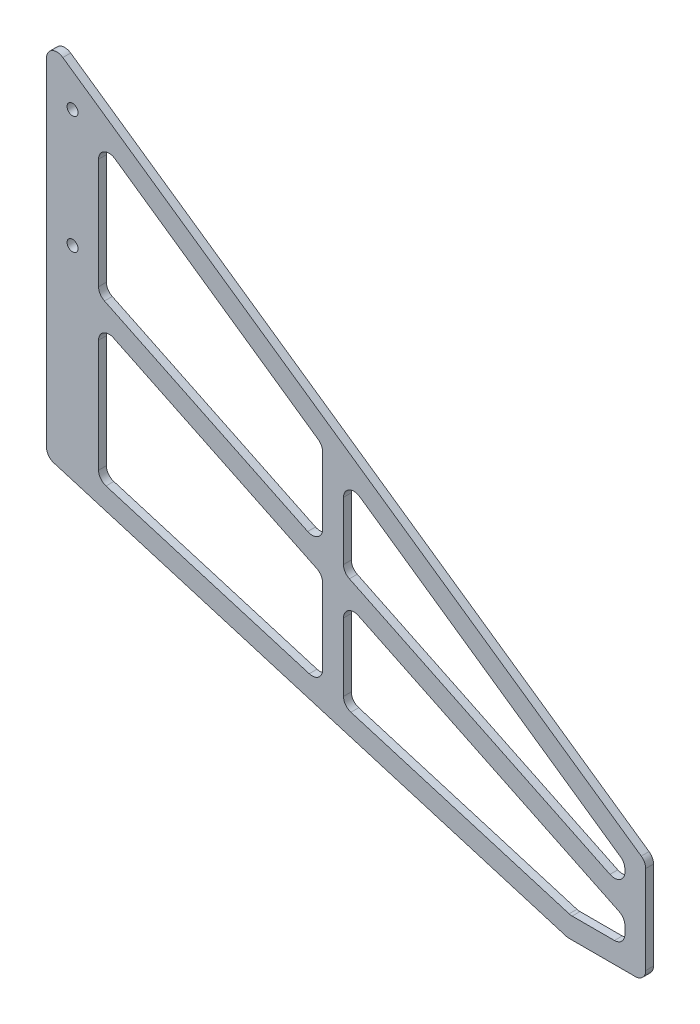
SolidWorks part; units mm, degrees
ref_plane "Спереди" through (0, 0, 0) normal (0, 0, 1) x (1, 0, 0)
ref_plane "Сверху" through (0, 0, 0) normal (0, 1, 0) x (1, 0, 0)
ref_plane "Справа" through (0, 0, 0) normal (1, 0, 0) x (0, 0, -1)
sketch "Эскиз1" plane through (0, 0, 0) normal (0, 0, 1) x (1, 0, 0)
  line L5 (0, 0) -> (0, 140)
  line L10 (0, 140) -> (230, -20)
  line L11 (230, -20) -> (230, -60)
  line L12 (230, -60) -> (200, -60)
  line L13 (200, -60) -> (0, 0)
  dimension "D1" = 230
  dimension "D2" = 40
  dimension "D3" = 30
  dimension "D4" = 140
  dimension "D5" = 60
extrude "Бобышка-Вытянуть1" add sketch "Эскиз1" along normal blind 3
sketch "Эскиз2" plane through (0, 0, 3) normal (0, 0, 1) x (1, 0, 0)
  line L0 (0, 140) -> (0, 0) construction
  circle A0 centre (10, 75) radius 2.1
  circle A1 centre (10, 120.2) radius 2.1
  dimension "D1" = 4.2
  dimension "D2" = 75
  dimension "D3" = 10
  dimension "D4" = 4.2
  dimension "D5" = 45.2
  dimension "D6" = 10
extrude "Вырез-Вытянуть1" cut sketch "Эскиз2" against normal blind 39
sketch "Эскиз5" plane through (0, 0, 3) normal (0, 0, 1) x (1, 0, 0)
  line L0 (222, -24.1801) -> (222, -33.649)
  line L1 (230, -60) -> (230, -20) construction
  line L2 (20, 59.3469) -> (222, -38.0901) construction
  line L3 (20, 63.788) -> (106, 22.3049)
  line L4 (20, 54.9059) -> (106, 13.4228)
  line L5 (20, 116.3416) -> (20, 63.788)
  line L6 (0, 140) -> (0, 0) construction
  line L7 (110, 53.7329) -> (110, -24.6478) construction
  line L8 (114, 50.9503) -> (114, 18.446)
  line L9 (106, 56.5155) -> (106, 22.3049)
  line L10 (8, 5.9522) -> (201.1742, -52)
  line L11 (201.1742, -52) -> (222, -52)
  line L12 (222, -52) -> (222, -24.1801)
  line L13 (222, -24.1801) -> (8, 124.6894)
  line L14 (8, 124.6894) -> (8, 5.9522)
  line L15 (20, 2.3522) -> (106, -23.4478)
  line L16 (201.1742, -52) -> (222, -52)
  line L18 (222, -24.1801) -> (114, 50.9503)
  line L20 (114, 18.446) -> (222, -33.649)
  line L21 (106, 13.4228) -> (106, -23.4478)
  line L22 (114, 9.5639) -> (114, -25.8478)
  line L23 (114, 9.5639) -> (222, -42.5311)
  line L24 (106, 56.5155) -> (20, 116.3416)
  line L25 (20, 54.9059) -> (20, 2.3522)
  line L26 (114, -25.8478) -> (201.1742, -52)
  line L27 (222, -42.5311) -> (222, -52)
  dimension "D2" = 20
  dimension "D3" = 8
  dimension "D4" = 8
  dimension "D5" = 4
  dimension "D6" = 8
  dimension "D7" = 4
  dimension "D8" = 90
  dimension "D1" = 8
sketch "Эскиз6" plane through (0, 0, 0) normal (0, 0, 1) x (1, 0, 0)
  line L1 (200.7338, -55) -> (220, -55) construction
  line L2 (20, -0.7798) -> (200.7338, -55) construction
  line L3 (20, 119.9961) -> (20, -0.7798) construction
  line L4 (220, -19.1343) -> (20, 119.9961) construction
  line L5 (220, -55) -> (220, -19.1343)
  line L6 (200.7338, -55) -> (220, -55)
  line L7 (20, -0.7798) -> (200.7338, -55)
  line L8 (20, 119.9961) -> (20, -0.7798)
  line L9 (220, -19.1343) -> (20, 119.9961)
  line L10 (178.4118, 9.7966) -> (178.4118, -48.3034) construction
  line L11 (171.4118, -46.2034) -> (220, -46.2034)
  line L13 (171.4118, -18.2034) -> (171.4118, -46.2034)
  line L14 (185.1618, -18.2034) -> (185.1618, -46.2034)
  line L15 (171.4118, -18.2034) -> (174.4118, -18.2034)
  line L16 (174.4118, -18.2034) -> (174.4118, 12.5792)
  line L17 (182.4118, -18.2034) -> (182.4118, 7.014)
  line L18 (182.4118, -18.2034) -> (185.1618, -18.2034)
  dimension "D1" = 28
  dimension "D2" = 4
  dimension "D3" = 6.75
  dimension "D4" = 8
  dimension "D5" = 3
  dimension "D6" = 28
sketch "Эскиз7" plane through (0, 0, 0) normal (0, 0, 1) x (1, 0, 0)
  line L0 (114.9827, -29.2747) -> (135.632, 39.5564) construction
  line L11 (20, -0.7798) -> (200.7338, -55) construction
  line L16 (220, -19.1343) -> (20, 119.9961) construction
  line L17 (105.3087, -23.2404) -> (126.3808, -29.562)
  line L18 (126.3808, -29.562) -> (142.7597, 25.0341)
  line L19 (142.7597, 25.0341) -> (121.6875, 31.3557)
  line L20 (121.6875, 31.3557) -> (106.7454, -18.4512)
  line L25 (97.646, -20.9416) -> (20, 2.3522)
  line L26 (20, 119.9961) -> (20, -0.7798) construction
  line L27 (134.0434, -31.8608) -> (201.1742, -52)
  line L28 (200.7338, -55) -> (220, -55) construction
  line L29 (20, 116.3416) -> (118.3134, 47.9497)
  line L31 (20, 59.6081) -> (220, -37.0672) construction
  line L32 (151.1365, 25.1162) -> (220.1765, -22.9116)
  line L33 (230, -20) -> (0, 140) construction
  line L34 (134.0434, -31.8608) -> (151.1365, 25.1162)
  line L35 (134.0434, -31.8608) -> (152.7211, 30.3979) construction
  line L36 (118.3134, 47.9497) -> (110.0809, 20.5079)
  line L37 (116.3237, 41.3171) -> (97.646, -20.9416) construction
  line L39 (152.7211, 30.3979) -> (116.3237, 41.3171) construction
  line L41 (20, -0.7798) -> (200.7338, -55)
  line L44 (20, -0.7798) -> (20, 2.3522)
  line L46 (220.1765, -13.1662) -> (20, 126.087)
  line L47 (20, 116.3416) -> (20, 126.087)
  line L48 (220.1765, -22.9116) -> (220.1765, -13.1662)
  line L49 (20, 64.0509) -> (110.0809, 20.5079)
  line L50 (20, 55.1653) -> (107.7528, 12.7477)
  line L51 (220, -52) -> (220, -55)
  line L52 (99.0828, -16.1524) -> (106.7454, -18.4512)
  line L53 (97.646, -20.9416) -> (105.3087, -23.2404)
  line L54 (121.6875, 31.3557) -> (105.3087, -23.2404) construction
  line L55 (107.7528, 12.7477) -> (99.0828, -16.1524)
  line L56 (20, 64.0509) -> (20, 55.1653)
  line L57 (201.1742, -52) -> (220, -52)
  line L59 (220, -55) -> (200.7338, -55)
  dimension "D1" = 22
  dimension "D2" = 11
  dimension "D3" = 57
  dimension "D4" = 3
  dimension "D6" = 3
  dimension "D7" = 3
  dimension "D8" = 4
  dimension "D9" = 4
  dimension "D10" = 5
  dimension "D11" = 3
  dimension "D5" = 8
extrude "Вырез-Вытянуть2" cut sketch "Эскиз5" against normal blind 10
fillet "Скругление1" radius 4 5 edges at (230, -20, 1.5) (230, -60, 1.5) (200, -60, 1.5) (0, 140, 1.5) (0, 0, 1.5)
fillet "Скругление2" radius 4 17 edges at (20, 54.9059, 1.5) (106, -23.4478, 1.5) (106, 13.4228, 1.5) (114, 9.5639, 1.5) (222, -42.5311, 1.5) (222, -52, 1.5) (201.1742, -52, 1.5) (114, -25.8478, 1.5) (20, 2.3522, 1.5) (20, 63.788, 1.5) (20, 116.3416, 1.5) (106, 22.3049, 1.5) (106, 56.5155, 1.5) (114, 18.446, 1.5) (114, 50.9503, 1.5) (222, -33.649, 1.5) (222, -24.1801, 1.5)
equation "\"13б5\"=20.1238"
